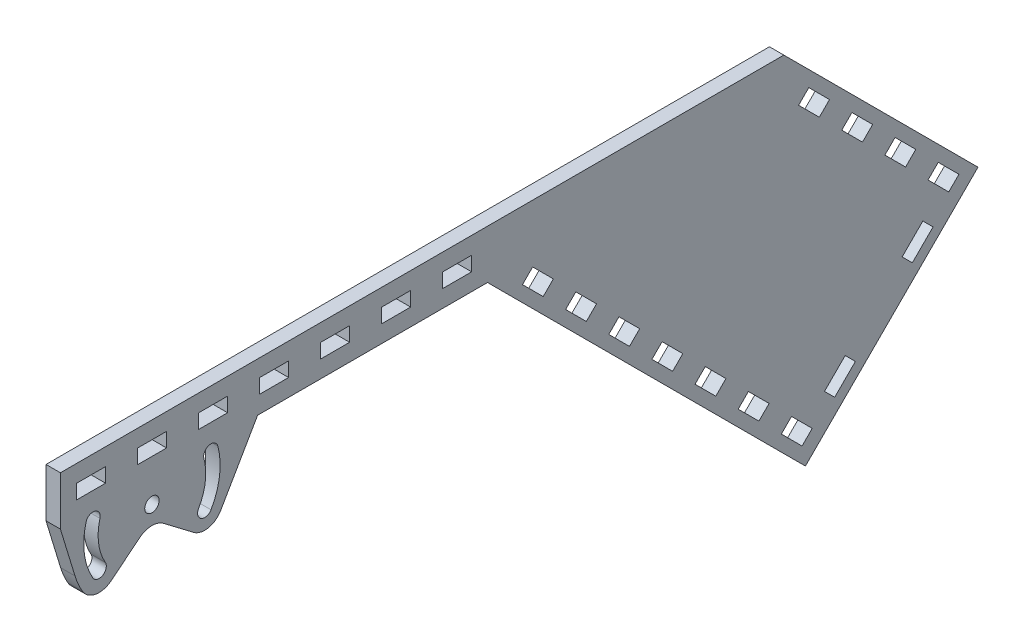
SolidWorks part; units mm, degrees
ref_plane "Front Plane" through (0, 0, 0) normal (0, 0, 1) x (1, 0, 0)
ref_plane "Top Plane" through (0, 0, 0) normal (0, 1, 0) x (1, 0, 0)
ref_plane "Right Plane" through (0, 0, 0) normal (1, 0, 0) x (0, 0, -1)
sketch "Sketch1" plane through (0, 0, 0) normal (1, 0, 0) x (0, 0, -1)
  line L6 (0, 0) -> (13.0982, 0) construction
  line L8 (0, 0) -> (12.2673, 3.287) construction
  line L9 (0, 0) -> (10.9985, -6.35) construction
  line L10 (9.0935, -9.6496) -> (-1.905, -3.2996)
  line L11 (21.997, 5.08) -> (14.2981, -8.255)
  line L12 (1.8452, 5.08) -> (21.997, 5.08) construction
  line L13 (21.997, 5.08) -> (69.85, 5.08)
  line L14 (69.85, 5.08) -> (136.0222, -61.0922)
  line L15 (136.0222, -61.0922) -> (171.9432, -25.1712)
  line L16 (171.9432, -25.1712) -> (131.532, 15.24)
  line L17 (131.532, 15.24) -> (-19.05, 15.24)
  line L18 (153.9827, -43.1317) -> (95.611, 15.24) construction
  line L19 (-3.2996, -1.905) -> (-7.3323, 5.08)
  line L20 (-7.3323, 5.08) -> (-19.05, 5.08)
  line L21 (-19.05, 5.08) -> (-19.05, 15.24)
  line L22 (136.0222, -61.0922) -> (66.0087, 8.9213) construction
  line L23 (136.0222, -61.0922) -> (141.4103, -55.704) construction
  line L24 (66.0087, 8.9213) -> (71.3969, 14.3094) construction
  line L25 (141.4103, -55.704) -> (71.3969, 14.3094) construction
  line L26 (171.9432, -25.1712) -> (132.9108, 13.8612) construction
  line L27 (171.9432, -25.1712) -> (166.555, -30.5593) construction
  line L28 (132.9108, 13.8612) -> (127.5227, 8.4731) construction
  line L29 (166.555, -30.5593) -> (127.5227, 8.4731) construction
  line L30 (143.2064, -48.5198) -> (159.3708, -32.3554) construction
  line L32 (0, 0) -> (-3.175, 0) construction
  line L33 (-3.175, 0) -> (-3.175, 10.16) construction
  line L34 (-3.175, 10.16) -> (0, 10.16) construction
  line L35 (0, 0) -> (-12.2673, 3.287) construction
  line L36 (0, 0) -> (-10.9985, -6.35) construction
  line L37 (-19.05, 5.08) -> (-16.0121, -4.8826)
  line L38 (-8.4585, -9.4917) -> (-2.5437, -4.7096)
  line L39 (9.0935, -9.6496) -> (-1.905, -3.2996)
  line L40 (8.6924, -9.3828) -> (2.4489, -4.6353)
  line L41 (2.4489, -4.6353) -> (1.1357, -3.6368) construction
  line L42 (-1.2601, -3.6719) -> (-1.1937, -3.6182) construction
  line L43 (-2.5437, -4.7096) -> (-1.2601, -3.6719) construction
  circle A0 centre (0, 0) radius 1.5
  circle A1 centre (0, 0) radius 3.81 construction
  arc A2 (10.9985, -6.35) -> (12.2673, 3.287) centre (0, 0) ccw construction
  arc A3 (12.2976, -7.1) -> (13.7161, 3.6752) centre (0, 0) ccw
  arc A4 (9.6995, -5.6) -> (10.8184, 2.8988) centre (0, 0) ccw
  arc A5 (9.6995, -5.6) -> (12.2976, -7.1) centre (10.9985, -6.35) ccw
  arc A6 (13.7161, 3.6752) -> (10.8184, 2.8988) centre (12.2673, 3.287) ccw
  arc A7 (10.9985, -6.35) -> (12.2673, 3.287) centre (0, 0) ccw construction
  arc A8 (14.2981, -8.255) -> (15.9474, 4.2731) centre (0, 0) ccw construction
  arc A9 (7.699, -4.445) -> (8.5871, 2.3009) centre (0, 0) ccw construction
  arc A10 (7.699, -4.445) -> (14.2981, -8.255) centre (10.9985, -6.35) ccw construction
  arc A11 (15.9474, 4.2731) -> (8.5871, 2.3009) centre (12.2673, 3.287) ccw construction
  arc A12 (9.0935, -9.6496) -> (14.2981, -8.255) centre (10.9985, -6.35) ccw
  arc A13 (-10.9985, -6.35) -> (-12.2673, 3.287) centre (0, 0) cw construction
  arc A14 (-1.905, -3.2996) -> (-3.2996, -1.905) centre (0, 0) cw
  arc A15 (-13.7161, 3.6752) -> (-12.2976, -7.1) centre (0, 0) ccw
  arc A16 (-10.8184, 2.8988) -> (-9.6995, -5.6) centre (0, 0) ccw
  arc A17 (-10.8184, 2.8988) -> (-13.7161, 3.6752) centre (-12.2673, 3.287) ccw
  arc A18 (-12.2976, -7.1) -> (-9.6995, -5.6) centre (-10.9985, -6.35) ccw
  arc A19 (-16.1696, 4.3326) -> (-14.4973, -8.37) centre (0, 0) ccw construction
  arc A20 (-14.4973, -8.37) -> (-7.4998, -4.33) centre (-10.9985, -6.35) ccw construction
  arc A21 (-8.3649, 2.2414) -> (-7.4998, -4.33) centre (0, 0) ccw construction
  arc A22 (-8.3649, 2.2414) -> (-16.1696, 4.3326) centre (-12.2673, 3.287) ccw construction
  arc A23 (-16.0121, -4.8826) -> (-14.4973, -8.37) centre (0, 0) ccw
  arc A24 (-14.4973, -8.37) -> (-8.4585, -9.4917) centre (-10.9985, -6.35) ccw
  arc A25 (-2.5437, -4.7096) -> (2.4489, -4.6353) centre (0, -7.8559) cw
  arc A26 (9.0935, -9.6496) -> (8.6924, -9.3828) centre (10.9985, -6.35) cw
  point P6 (12.5913, -1.6577)
  point P16 (12.5913, -1.6577)
  point P51 (-12.5913, -1.6577)
  line B0 (135.3207, -57.1239) -> (131.0102, -52.8134)
  line B1 (135.3207, -57.1239) -> (137.442, -55.0026)
  line B2 (131.0102, -52.8134) -> (133.1315, -50.6921)
  line B3 (137.442, -55.0026) -> (133.1315, -50.6921)
  line B4 (135.3207, -57.1239) -> (133.1315, -50.6921) construction
  line B5 (131.0102, -52.8134) -> (137.442, -55.0026) construction
  line B6 (165.8536, -26.591) -> (161.5431, -22.2805)
  line B7 (165.8536, -26.591) -> (167.9749, -24.4697)
  line B8 (161.5431, -22.2805) -> (163.6644, -20.1592)
  line B9 (167.9749, -24.4697) -> (163.6644, -20.1592)
  line B10 (165.8536, -26.591) -> (163.6644, -20.1592) construction
  line B11 (161.5431, -22.2805) -> (167.9749, -24.4697) construction
  line B12 (126.3405, -48.1436) -> (122.0299, -43.8331)
  line B13 (126.3405, -48.1436) -> (128.4618, -46.0223)
  line B14 (122.0299, -43.8331) -> (124.1513, -41.7118)
  line B15 (128.4618, -46.0223) -> (124.1513, -41.7118)
  line B16 (126.3405, -48.1436) -> (124.1513, -41.7118) construction
  line B17 (122.0299, -43.8331) -> (128.4618, -46.0223) construction
  line B18 (117.3602, -39.1634) -> (113.0497, -34.8529)
  line B19 (117.3602, -39.1634) -> (119.4815, -37.0421)
  line B20 (113.0497, -34.8529) -> (115.171, -32.7315)
  line B21 (119.4815, -37.0421) -> (115.171, -32.7315)
  line B22 (117.3602, -39.1634) -> (115.171, -32.7315) construction
  line B23 (113.0497, -34.8529) -> (119.4815, -37.0421) construction
  line B24 (108.38, -30.1831) -> (104.0694, -25.8726)
  line B25 (108.38, -30.1831) -> (110.5013, -28.0618)
  line B26 (104.0694, -25.8726) -> (106.1908, -23.7513)
  line B27 (110.5013, -28.0618) -> (106.1908, -23.7513)
  line B28 (108.38, -30.1831) -> (106.1908, -23.7513) construction
  line B29 (104.0694, -25.8726) -> (110.5013, -28.0618) construction
  line B30 (99.3997, -21.2029) -> (95.0892, -16.8923)
  line B31 (99.3997, -21.2029) -> (101.521, -19.0815)
  line B32 (95.0892, -16.8923) -> (97.2105, -14.771)
  line B33 (101.521, -19.0815) -> (97.2105, -14.771)
  line B34 (99.3997, -21.2029) -> (97.2105, -14.771) construction
  line B35 (95.0892, -16.8923) -> (101.521, -19.0815) construction
  line B36 (90.4194, -12.2226) -> (86.1089, -7.9121)
  line B37 (90.4194, -12.2226) -> (92.5408, -10.1013)
  line B38 (86.1089, -7.9121) -> (88.2302, -5.7908)
  line B39 (92.5408, -10.1013) -> (88.2302, -5.7908)
  line B40 (90.4194, -12.2226) -> (88.2302, -5.7908) construction
  line B41 (86.1089, -7.9121) -> (92.5408, -10.1013) construction
  line B42 (81.4392, -3.2424) -> (77.1287, 1.0682)
  line B43 (81.4392, -3.2424) -> (83.5605, -1.121)
  line B44 (77.1287, 1.0682) -> (79.25, 3.1895)
  line B45 (83.5605, -1.121) -> (79.25, 3.1895)
  line B46 (81.4392, -3.2424) -> (79.25, 3.1895) construction
  line B47 (77.1287, 1.0682) -> (83.5605, -1.121) construction
  line B48 (156.8733, -17.6108) -> (152.5628, -13.3002)
  line B49 (156.8733, -17.6108) -> (158.9947, -15.4894)
  line B50 (152.5628, -13.3002) -> (154.6841, -11.1789)
  line B51 (158.9947, -15.4894) -> (154.6841, -11.1789)
  line B52 (156.8733, -17.6108) -> (154.6841, -11.1789) construction
  line B53 (152.5628, -13.3002) -> (158.9947, -15.4894) construction
  line B54 (147.8931, -8.6305) -> (143.5826, -4.32)
  line B55 (147.8931, -8.6305) -> (150.0144, -6.5092)
  line B56 (143.5826, -4.32) -> (145.7039, -2.1987)
  line B57 (150.0144, -6.5092) -> (145.7039, -2.1987)
  line B58 (147.8931, -8.6305) -> (145.7039, -2.1987) construction
  line B59 (143.5826, -4.32) -> (150.0144, -6.5092) construction
  line B60 (138.9128, 0.3497) -> (134.6023, 4.6603)
  line B61 (138.9128, 0.3497) -> (141.0341, 2.4711)
  line B62 (134.6023, 4.6603) -> (136.7236, 6.7816)
  line B63 (141.0341, 2.4711) -> (136.7236, 6.7816)
  line B64 (138.9128, 0.3497) -> (136.7236, 6.7816) construction
  line B65 (134.6023, 4.6603) -> (141.0341, 2.4711) construction
  line B66 (139.9905, -49.6144) -> (144.301, -45.3039)
  line B67 (139.9905, -49.6144) -> (142.1118, -51.7357)
  line B68 (144.301, -45.3039) -> (146.4223, -47.4252)
  line B69 (142.1118, -51.7357) -> (146.4223, -47.4252)
  line B70 (139.9905, -49.6144) -> (146.4223, -47.4252) construction
  line B71 (144.301, -45.3039) -> (142.1118, -51.7357) construction
  line B72 (156.1549, -33.45) -> (160.4654, -29.1394)
  line B73 (156.1549, -33.45) -> (158.2762, -35.5713)
  line B74 (160.4654, -29.1394) -> (162.5868, -31.2608)
  line B75 (158.2762, -35.5713) -> (162.5868, -31.2608)
  line B76 (156.1549, -33.45) -> (162.5868, -31.2608) construction
  line B77 (160.4654, -29.1394) -> (158.2762, -35.5713) construction
  line B78 (3.048, 8.66) -> (-3.048, 8.66)
  line B79 (3.048, 8.66) -> (3.048, 11.66)
  line B80 (-3.048, 8.66) -> (-3.048, 11.66)
  line B81 (3.048, 11.66) -> (-3.048, 11.66)
  line B82 (3.048, 8.66) -> (-3.048, 11.66) construction
  line B83 (-3.048, 8.66) -> (3.048, 11.66) construction
  line B84 (15.748, 8.66) -> (9.652, 8.66)
  line B85 (15.748, 8.66) -> (15.748, 11.66)
  line B86 (9.652, 8.66) -> (9.652, 11.66)
  line B87 (15.748, 11.66) -> (9.652, 11.66)
  line B88 (15.748, 8.66) -> (9.652, 11.66) construction
  line B89 (9.652, 8.66) -> (15.748, 11.66) construction
  line B90 (28.448, 8.66) -> (22.352, 8.66)
  line B91 (28.448, 8.66) -> (28.448, 11.66)
  line B92 (22.352, 8.66) -> (22.352, 11.66)
  line B93 (28.448, 11.66) -> (22.352, 11.66)
  line B94 (28.448, 8.66) -> (22.352, 11.66) construction
  line B95 (22.352, 8.66) -> (28.448, 11.66) construction
  line B96 (41.148, 8.66) -> (35.052, 8.66)
  line B97 (41.148, 8.66) -> (41.148, 11.66)
  line B98 (35.052, 8.66) -> (35.052, 11.66)
  line B99 (41.148, 11.66) -> (35.052, 11.66)
  line B100 (41.148, 8.66) -> (35.052, 11.66) construction
  line B101 (35.052, 8.66) -> (41.148, 11.66) construction
  line B102 (53.848, 8.66) -> (47.752, 8.66)
  line B103 (53.848, 8.66) -> (53.848, 11.66)
  line B104 (47.752, 8.66) -> (47.752, 11.66)
  line B105 (53.848, 11.66) -> (47.752, 11.66)
  line B106 (53.848, 8.66) -> (47.752, 11.66) construction
  line B107 (47.752, 8.66) -> (53.848, 11.66) construction
  line B108 (66.548, 8.66) -> (60.452, 8.66)
  line B109 (66.548, 8.66) -> (66.548, 11.66)
  line B110 (60.452, 8.66) -> (60.452, 11.66)
  line B111 (66.548, 11.66) -> (60.452, 11.66)
  line B112 (66.548, 8.66) -> (60.452, 11.66) construction
  line B113 (60.452, 8.66) -> (66.548, 11.66) construction
  line B114 (-9.652, 8.66) -> (-15.748, 8.66)
  line B115 (-9.652, 8.66) -> (-9.652, 11.66)
  line B116 (-15.748, 8.66) -> (-15.748, 11.66)
  line B117 (-9.652, 11.66) -> (-15.748, 11.66)
  line B118 (-9.652, 8.66) -> (-15.748, 11.66) construction
  line B119 (-15.748, 8.66) -> (-9.652, 11.66) construction
  dimension "D1" = 3
  dimension "D2" = 7.62
  dimension "D3" = 3
  dimension "D13" = 7.62
  dimension "D16" = 60
  dimension "D4" = 12.7
  dimension "D5" = 15
  dimension "D6" = 30
  dimension "D7" = 5.08
  dimension "D8" = 3.81
  dimension "D9" = 45
  dimension "D10" = 10.16
  dimension "D11" = 50.8
  dimension "D12" = 82.55
  dimension "D14" = 69.85
  dimension "D15" = 7.62
  dimension "D17" = 7.62
  dimension "D18" = 6.35
  dimension "D19" = 6.35
  dimension "D20" = 3.81
  dimension "D21" = 3.81
  dimension "D24" = 6.35
  dimension "D25" = 3.81
  dimension "D26" = 6.35
  dimension "D27" = 3.175
  dimension "D28" = 3.175
  dimension "D29" = 12.7
  dimension "D30" = 12.7
  dimension "D31" = 5.08
  dimension "D33" = 12.7
  dimension "D34" = 12.7
  dimension "D35" = 6.35
  dimension "D36" = 15
  dimension "D37" = 30
  dimension "D38" = 2.54
  dimension "D22" = 7
  dimension "D23" = 4
  dimension "D32" = 6
sketch_block_instance "Block1-1"
sketch_block "Block1" parameters "D1"=3, "D2"=6.096
sketch_block_instance "Block1-2"
sketch_block_instance "Block1-3"
sketch_block_instance "Block1-4"
sketch_block_instance "Block1-5"
sketch_block_instance "Block1-6"
sketch_block_instance "Block1-7"
sketch_block_instance "Block1-8"
sketch_block_instance "Block1-9"
sketch_block_instance "Block1-10"
sketch_block_instance "Block1-11"
sketch_block_instance "Block1-12"
sketch_block_instance "Block1-13"
sketch_block_instance "Block1-20"
sketch_block_instance "Block1-21"
sketch_block_instance "Block1-22"
sketch_block_instance "Block1-23"
sketch_block_instance "Block1-24"
sketch_block_instance "Block1-25"
sketch_block_instance "Block1-26"
extrude "Boss-Extrude1" add sketch "Sketch1" along normal mid plane 3 contours A14 L10 A12 L11 L13 L14 L15 L16 L17 L21 L20 L19 B117 B115 B114 B116 B111 B109 B108 B110 B105 B103 B102 B104 B99 B97 B96 B98 B93 B91 B90 B92 B87 B85 B84 B86 B81 B79 B78 B80 B75 B73 | A23 A24 L38 A12 L10 A14 L19 L20 L37 A18 A15 A17 A16
equation "\"PlateThickness\"=0.11811"
equation "\"D1@Boss-Extrude1\"=\"PlateThickness\""
